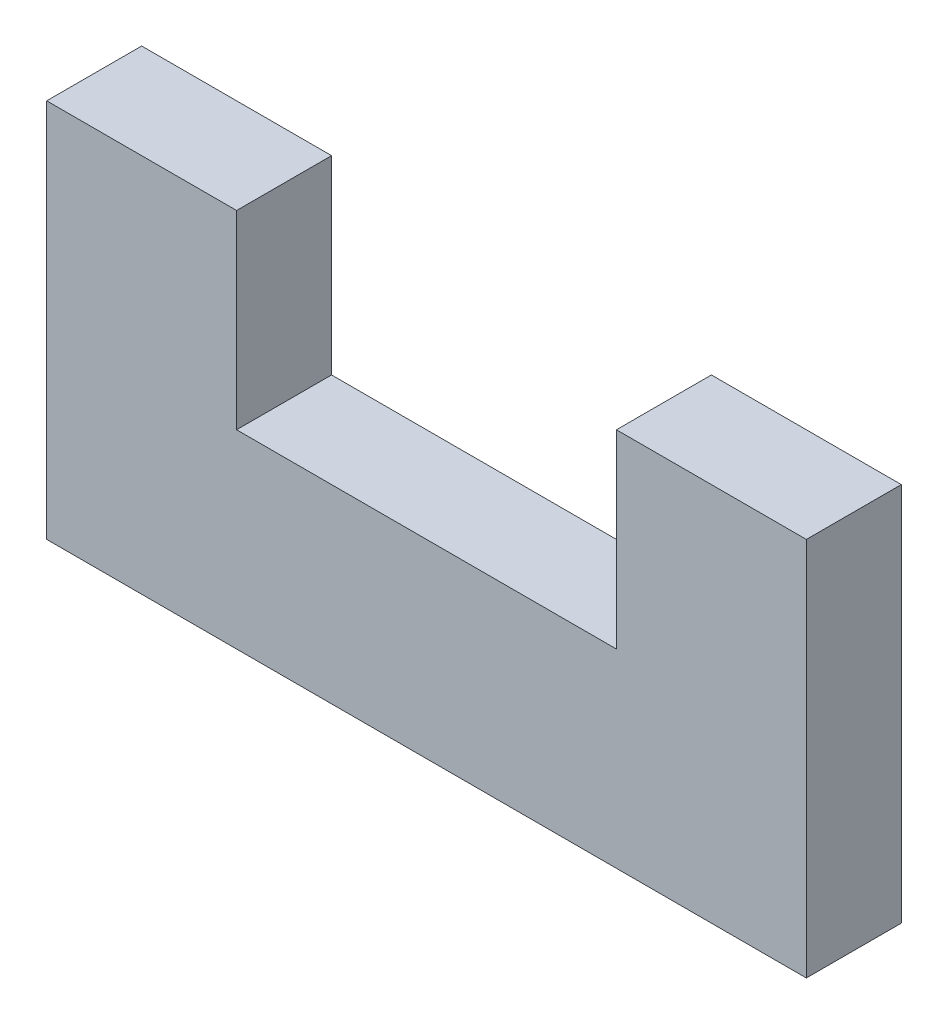
SolidWorks part; units mm, degrees
ref_plane "Front Plane" through (0, 0, 0) normal (0, 0, 1) x (1, 0, 0)
ref_plane "Top Plane" through (0, 0, 0) normal (0, 1, 0) x (1, 0, 0)
ref_plane "Right Plane" through (0, 0, 0) normal (1, 0, 0) x (0, 0, -1)
sketch "Sketch1" plane through (0, 0, 0) normal (0, 0, 1) x (1, 0, 0)
  line L0 (3, -1.5) -> (6, -1.5) construction
  line L2 (-3, 1.5) -> (-3, -1.5)
  line L3 (-3, -1.5) -> (3, -1.5)
  line L4 (3, 1.5) -> (3, -1.5)
  line L5 (-3, 1.5) -> (3, -1.5) construction
  line L6 (-3, -1.5) -> (3, 1.5) construction
  line L7 (-6, 1.5) -> (-3, 1.5)
  line L8 (-6, 1.5) -> (-6, -4.5)
  line L9 (-6, -4.5) -> (6, -4.5)
  line L10 (6, 1.5) -> (6, -4.5)
  line L11 (0, -1.5) -> (0, -4.5) construction
  line L12 (-3, -1.5) -> (-6, -1.5) construction
  line L13 (3, 1.5) -> (6, 1.5)
  point P0 (0, 0)
  dimension "D1" = 6
  dimension "D2" = 3
  dimension "D3" = 3
extrude "Boss-Extrude1" add sketch "Sketch1" along normal blind 1.5
